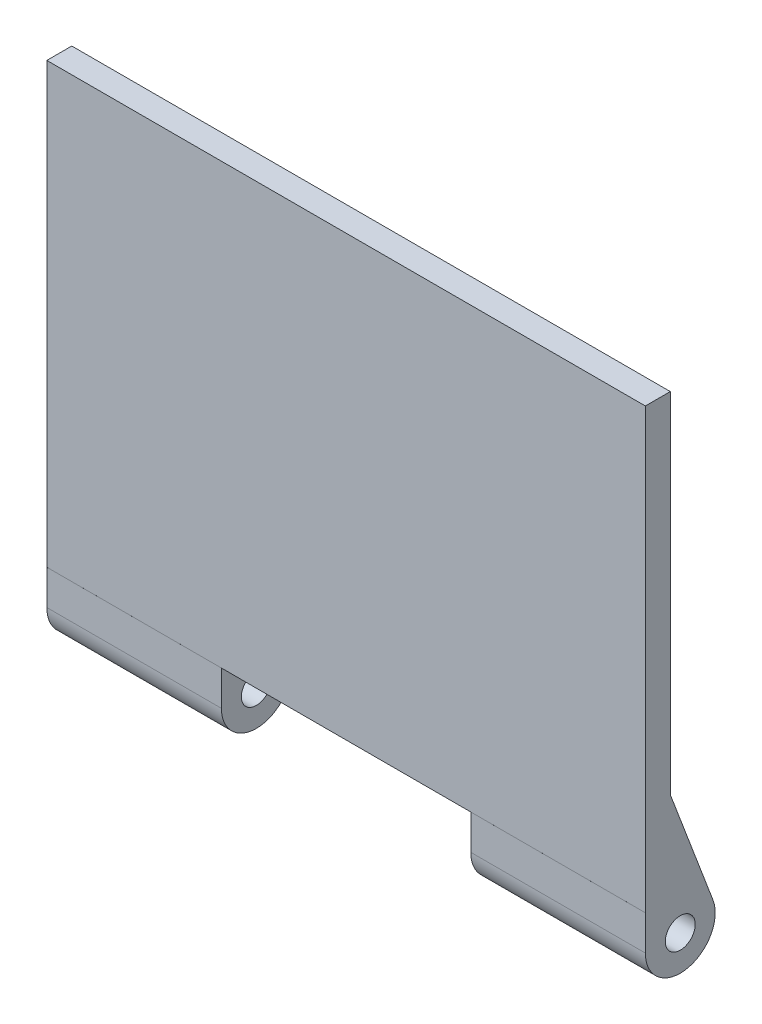
SolidWorks part; units mm, degrees
ref_plane "前视基准面" through (0, 0, 0) normal (0, 0, 1) x (1, 0, 0)
ref_plane "上视基准面" through (0, 0, 0) normal (0, 1, 0) x (1, 0, 0)
ref_plane "右视基准面" through (0, 0, 0) normal (1, 0, 0) x (0, 0, -1)
sketch "草图1" plane through (0, 0, 0) normal (0, 0, 1) x (1, 0, 0)
  line L1 (-30, -22) -> (30, -22)
  line L2 (-30, -22) -> (-30, 22)
  line L3 (-30, 22) -> (30, 22)
  line L4 (30, -22) -> (30, 22)
  point P0 (0, 0)
extrude "凸台-拉伸3" add sketch "草图1" along normal blind 2.5
sketch "草图4" plane through (30, 0, 0) normal (1, 0, 0) x (0, 0, -1)
  line L3 (0, -22) -> (0, -13)
  line L5 (-2.5006, -22) -> (-2.5006, -25.5)
  line L6 (-2.5, -22) -> (0, -22) construction
  line L8 (0, -22) -> (0, 22) construction
  line L10 (0, -13) -> (4.2718, -24.2584)
  line L11 (0, -22) -> (-2.5006, -22)
  circle A2 centre (0.9994, -25.5) radius 1.5
  arc A3 (-2.5006, -25.5) -> (4.2718, -24.2584) centre (0.9994, -25.5) ccw
extrude "凸台-拉伸4" add sketch "草图4" against normal blind 17.5
sketch "草图5" plane through (-30, 0, 0) normal (-1, 0, 0) x (0, 0, 1)
  line L5 (2.5, -22) -> (0, -22)
  line L6 (0, -22) -> (0, -13)
  line L7 (0, -13) -> (-4.2718, -24.2584)
  line L8 (2.5006, -25.5) -> (2.5006, -22)
  line L9 (2.5006, -22) -> (2.5, -22)
  line L10 (2.5, -22) -> (0, -22)
  line L11 (0, -22) -> (0, -13)
  line L12 (0, -13) -> (-4.2718, -24.2584)
  line L13 (2.5006, -25.5) -> (2.5006, -22)
  line L14 (2.5006, -22) -> (2.5, -22)
  circle A1 centre (-0.9994, -25.5) radius 1.5
  circle A2 centre (-0.9994, -25.5) radius 1.5
  arc A3 (-4.2718, -24.2584) -> (2.5006, -25.5) centre (-0.9994, -25.5) ccw
  arc A4 (-4.2718, -24.2584) -> (2.5006, -25.5) centre (-0.9994, -25.5) ccw
  dimension "D1" = 0
  dimension "D2" = 0
extrude "凸台-拉伸5" add sketch "草图5" against normal blind 17.5
